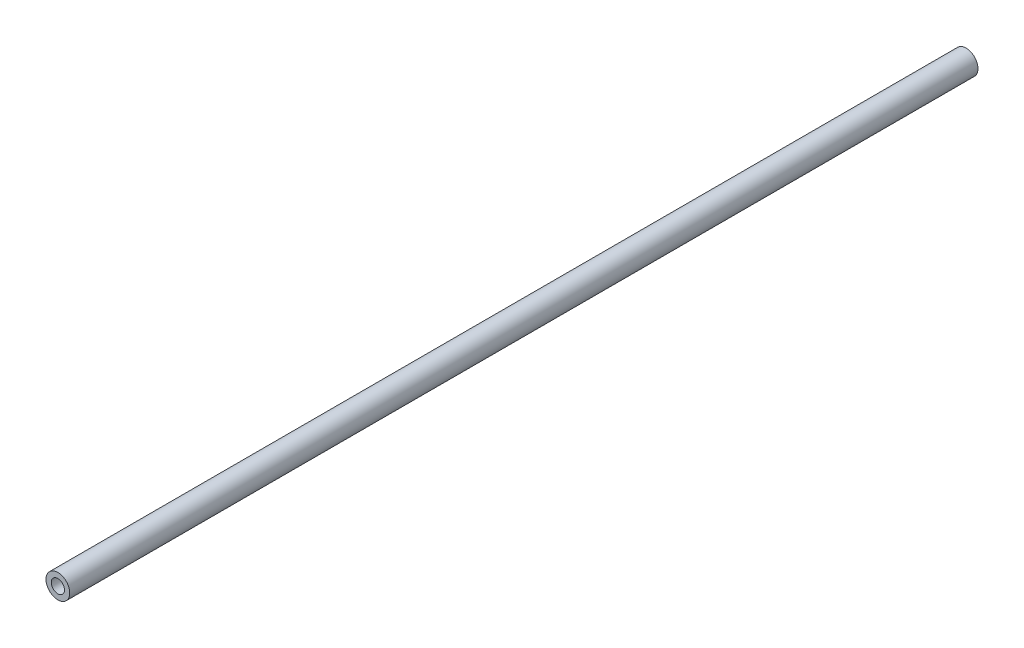
SolidWorks part; units mm, degrees
ref_plane "Front Plane" through (0, 0, 0) normal (0, 0, 1) x (1, 0, 0)
ref_plane "Top Plane" through (0, 0, 0) normal (0, 1, 0) x (1, 0, 0)
ref_plane "Right Plane" through (0, 0, 0) normal (1, 0, 0) x (0, 0, -1)
sketch "Sketch32" plane through (0, 0, 0) normal (0, 0, 1) x (1, 0, 0)
  circle A0 centre (0, 0) radius 8.55
  circle A1 centre (0, 0) radius 4.765
  dimension "D1" = 17.1
  dimension "D2" = 9.53
extrude "Boss-Extrude1" add sketch "Sketch32" along normal blind 653.17
